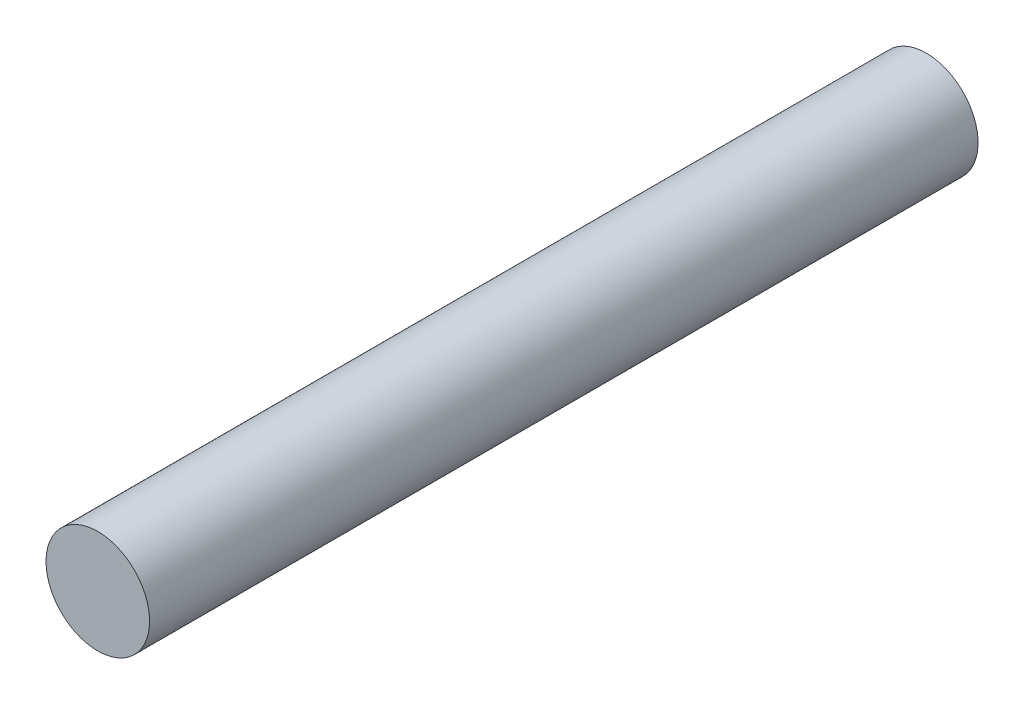
SolidWorks part; units mm, degrees
ref_plane "Front Plane" through (0, 0, 0) normal (0, 0, 1) x (1, 0, 0)
ref_plane "Top Plane" through (0, 0, 0) normal (0, 1, 0) x (1, 0, 0)
ref_plane "Right Plane" through (0, 0, 0) normal (1, 0, 0) x (0, 0, -1)
sketch "Sketch1" plane through (0, 0, 0) normal (0, 0, 1) x (1, 0, 0)
  circle A0 centre (0, 0) radius 6.25
  dimension "D1" = 12.5
extrude "Boss-Extrude1" add sketch "Sketch1" along normal blind 100
